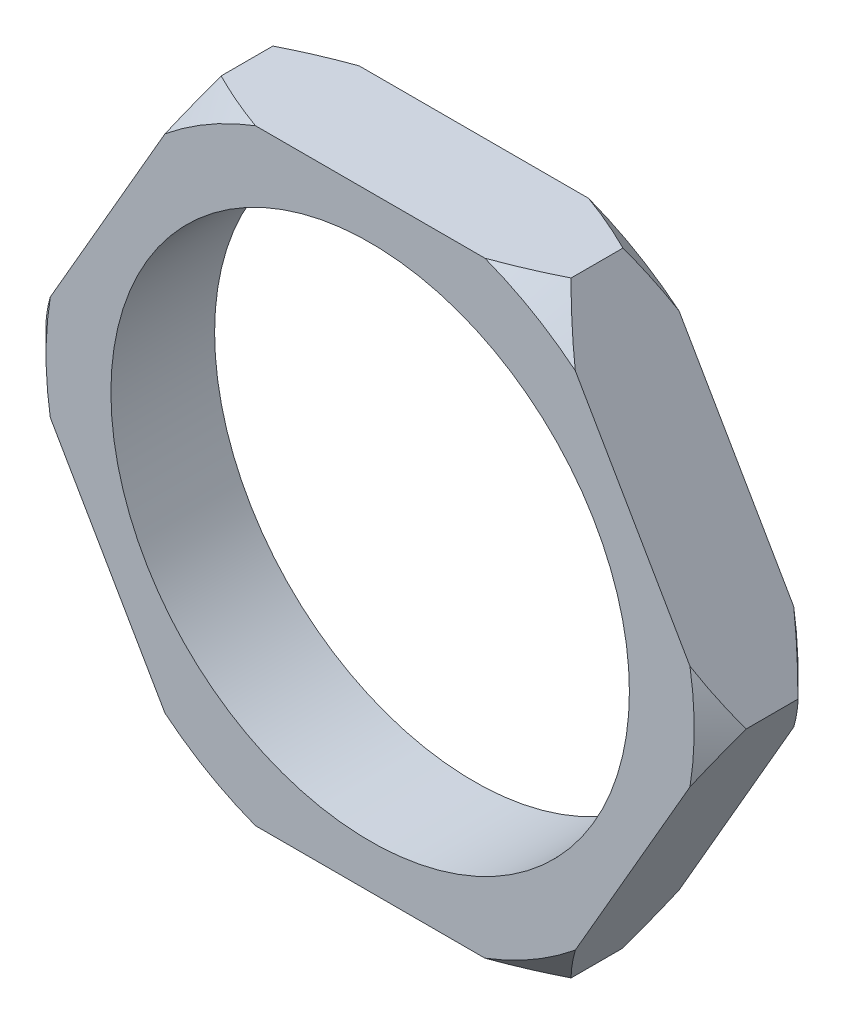
SolidWorks part; units mm, degrees
ref_plane "Front Plane" through (0, 0, 0) normal (0, 0, 1) x (1, 0, 0)
ref_plane "Top Plane" through (0, 0, 0) normal (0, 1, 0) x (1, 0, 0)
ref_plane "Right Plane" through (0, 0, 0) normal (1, 0, 0) x (0, 0, -1)
sketch "Sketch1" plane through (0, 0, 0) normal (0, 0, 1) x (1, 0, 0)
  line L1 (6.75, -11.6913) -> (13.5, 0)
  line L2 (13.5, 0) -> (6.75, 11.6913)
  line L3 (6.75, 11.6913) -> (-6.75, 11.6913)
  line L4 (-6.75, 11.6913) -> (-13.5, 0)
  line L5 (-13.5, 0) -> (-6.75, -11.6913)
  line L6 (-6.75, -11.6913) -> (6.75, -11.6913)
  circle A0 centre (0, 0) radius 10
  circle A1 centre (0, 0) radius 11.6913 construction
  point P3 (0, 11.6913)
  dimension "D1" = 20
  dimension "D2" = 27
extrude "Boss-Extrude1" add sketch "Sketch1" along normal mid plane 4
sketch "Sketch2" plane through (0, 11.6913, 0) normal (0, 1, 0) x (1, 0, 0)
  line L0 (-12.5, 2) -> (-13.5, 1)
  line L1 (-6.75, 2) -> (-13.5, 2) construction
  line L2 (-13.5, -2) -> (-13.5, 2) construction
  line L3 (-13.5, 1) -> (-13.5, 2)
  line L4 (-13.5, 2) -> (-12.5, 2)
  line L5 (-12.5, 2) -> (0, 2) construction
  line L6 (0, 2) -> (0, -2) construction
  line L7 (6.75, -2) -> (-6.75, -2) construction
  point P6 (0, -4)
  dimension "D1" = 1
  dimension "D2" = 1
sketch "Sketch4" plane through (0, 0, 0) normal (0, 1, 0) x (1, 0, 0)
  line L0 (0, 2) -> (0, -2) construction
  line L1 (-12.5, 2) -> (0, 2) construction
  line L2 (-13.5, 2) -> (-12.5, 2) construction
  line L3 (-13.5, 1) -> (-13.5, 2) construction
  line L4 (-12.5, 2) -> (-13.5, 1) construction
  line L5 (0, 2) -> (0, -2)
  line L6 (-12.5, 2) -> (0, 2)
  line L7 (-13.5, 2) -> (-12.5, 2)
  line L8 (-13.5, 1) -> (-13.5, 2)
  line L9 (-12.5, 2) -> (-13.5, 1)
revolve "Cut-Revolve1" cut sketch "Sketch4" angle 360 about L5
mirror "Mirror1" about plane through (0, 0, 0) normal (0, 0, 1) of "Cut-Revolve1"
